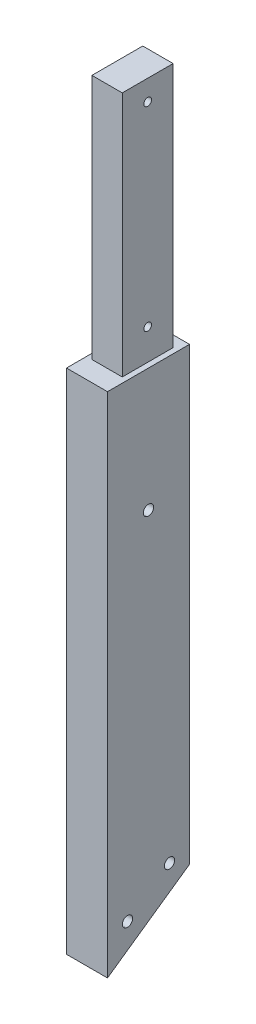
SolidWorks part; units mm, degrees
material "6061-T6 (SS)"
ref_plane "Front Plane" through (0, 0, 0) normal (0, 0, 1) x (1, 0, 0)
ref_plane "Top Plane" through (0, 0, 0) normal (0, 1, 0) x (1, 0, 0)
ref_plane "Right Plane" through (0, 0, 0) normal (1, 0, 0) x (0, 0, -1)
sketch "Sketch1" plane through (0, 0, 0) normal (1, 0, 0) x (0, 0, -1)
  line L1 (-25.4, -157.2449) -> (25.4, -157.2449)
  line L2 (-25.4, -157.2449) -> (-25.4, 157.2449)
  line L3 (-25.4, 157.2449) -> (25.4, 157.2449)
  line L4 (25.4, -157.2449) -> (25.4, 157.2449)
  line L5 (-25.4, -157.2449) -> (25.4, 157.2449) construction
  line L6 (-25.4, 157.2449) -> (25.4, -157.2449) construction
  point P0 (0, 0)
  dimension "D1" = 314.4899
  dimension "D2" = 50.8
extrude "Boss-Extrude1" add sketch "Sketch1" along normal blind 25.4
sketch "Sketch2" plane through (25.4, 0, 0) normal (1, 0, 0) x (0, 0, -1)
  line L0 (-25.4, -157.2449) -> (25.4, -121.6744)
  line L1 (25.4, -157.2449) -> (25.4, 157.2449) construction
  line L2 (25.4, -121.6744) -> (50.8, -121.6744)
  line L3 (50.8, -121.6744) -> (50.8, -172.4744)
  line L4 (50.8, -172.4744) -> (-25.4, -172.4744)
  line L5 (-25.4, -172.4744) -> (-25.4, -157.2449)
  line L6 (-25.4, -157.2449) -> (25.4, -157.2449) construction
  dimension "D1" = 35
  dimension "D2" = 76.2
  dimension "D3" = 50.8
extrude "Cut-Extrude1" cut sketch "Sketch2" against normal through all
sketch "Sketch3" plane through (25.4, 0, 0) normal (1, 0, 0) x (0, 0, -1)
  line L0 (13.004, -114.8503) -> (-13.004, -133.0614) construction
  line L1 (-13.004, -133.0614) -> (-25.4, -141.7411) construction
  line L2 (13.004, -114.8503) -> (25.4, -106.1706) construction
  line L3 (-25.4, 157.2449) -> (-25.4, -157.2449) construction
  line L4 (25.4, -121.6744) -> (25.4, 157.2449) construction
  line L6 (25.4, -121.6744) -> (-25.4, -157.2449) construction
  line L7 (-25.4, -141.7411) -> (-18.1156, -152.1443) construction
  line L8 (0, 157.2449) -> (0, 81.0449) construction
  line L9 (25.4, 157.2449) -> (-25.4, 157.2449) construction
  circle A0 centre (-13.004, -133.0614) radius 3.175
  circle A1 centre (13.004, -114.8503) radius 3.175
  circle A2 centre (0, 81.0449) radius 3.175
  dimension "D2" = 6.35
  dimension "D4" = 6.35
  dimension "D1" = 31.75
  dimension "D3" = 12.7
  dimension "D5" = 76.2
extrude "Cut-Extrude2" cut sketch "Sketch3" against normal through all
sketch "Sketch6" plane through (0, 157.2449, 0) normal (0, 1, 0) x (1, 0, 0)
  line L1 (0, 25.4) -> (25.4, 25.4)
  line L2 (0, 25.4) -> (0, -25.4)
  line L3 (0, -25.4) -> (25.4, -25.4)
  line L4 (25.4, 25.4) -> (25.4, -25.4)
extrude "Boss-Extrude3" add sketch "Sketch6" along normal blind 152.4
sketch "Sketch7" plane through (25.4, 0, 0) normal (1, 0, 0) x (0, 0, -1)
  line L0 (-25.4, 157.2449) -> (-25.4, 309.6449)
  line L2 (-25.4, 309.6449) -> (25.4, 309.6449) construction
  line L3 (-25.4, 309.6449) -> (-13.97, 309.6449)
  line L4 (-13.97, 309.6449) -> (-13.97, 163.5949)
  line L5 (39.294, 157.2449) -> (25.908, 157.2449)
  line L7 (39.294, 157.2449) -> (39.294, 309.6449)
  line L8 (39.294, 309.6449) -> (19.558, 309.6449)
  line L9 (19.558, 309.6449) -> (19.558, 163.5949)
  line L10 (-25.4, 157.2449) -> (-20.32, 157.2449)
  line L11 (-25.4, 309.6449) -> (-25.4, -157.2449) construction
  arc A0 (-20.32, 157.2449) -> (-13.97, 163.5949) centre (-20.32, 163.5949) ccw
  arc A1 (19.558, 163.5949) -> (25.908, 157.2449) centre (25.908, 163.5949) ccw
  dimension "D1" = 33.528
  dimension "D3" = 152.4
  dimension "D5" = 6.35
  dimension "D2" = 11.43
  dimension "D4" = 152.4
extrude "Cut-Extrude4" cut sketch "Sketch7" against normal through all
sketch "Sketch8" plane through (0, 0, 25.4) normal (0, 0, 1) x (1, 0, 0)
  line L0 (12.7, 309.6449) -> (12.7, 157.2449) construction
  line L1 (0, 309.6449) -> (25.4, 309.6449) construction
  line L2 (0, 157.2449) -> (25.4, 157.2449) construction
  line L3 (2.286, 309.6449) -> (-14.9016, 309.6449)
  line L4 (-14.9016, 309.6449) -> (-14.9016, 157.2449)
  line L5 (-14.9016, 157.2449) -> (-4.064, 157.2449)
  line L6 (2.286, 309.6449) -> (2.286, 163.5949)
  line L7 (23.114, 163.5949) -> (23.114, 309.6449)
  line L8 (23.114, 309.6449) -> (40.9833, 309.6449)
  line L9 (40.9833, 309.6449) -> (40.9833, 157.2449)
  line L10 (40.9833, 157.2449) -> (29.464, 157.2449)
  line L11 (2.286, 309.6449) -> (12.7, 309.6449) construction
  line L12 (12.7, 309.6449) -> (23.114, 309.6449) construction
  arc A0 (-4.064, 157.2449) -> (2.286, 163.5949) centre (-4.064, 163.5949) ccw
  arc A1 (23.114, 163.5949) -> (29.464, 157.2449) centre (29.464, 163.5949) ccw
  dimension "D2" = 6.35
  dimension "D1" = 20.828
extrude "Cut-Extrude5" cut sketch "Sketch8" against normal through all
sketch "Sketch5" plane through (23.114, 0, 0) normal (1, 0, 0) x (0, 0, -1)
  line L0 (2.794, 309.6449) -> (2.794, 157.2562) construction
  line L1 (19.558, 309.6449) -> (-13.97, 309.6449) construction
  line L4 (-25.4, 157.2449) -> (25.4, 157.2653) construction
  circle A0 centre (2.794, 296.9562) radius 2.3813
  circle A1 centre (2.794, 176.3062) radius 2.3812
  dimension "D1" = 4.7625
  dimension "D2" = 120.65
  dimension "D3" = 19.05
extrude "Cut-Extrude3" cut sketch "Sketch5" against normal through all
sketch "Sketch9" plane through (0, 309.6449, 0) normal (0, 1, 0) x (1, 0, 0)
  line L0 (22.098, 18.542) -> (3.302, 18.542)
  line L1 (3.302, 18.542) -> (3.302, -12.954)
  line L2 (3.302, -12.954) -> (22.098, -12.954)
  line L3 (22.098, -12.954) -> (22.098, 18.542)
  line L4 (22.098, 2.794) -> (12.7, 2.794)
  line L5 (12.7, -13.97) -> (12.7, 19.558)
  line L6 (2.286, -13.97) -> (23.114, -13.97) construction
  line L7 (2.286, 19.558) -> (23.114, 19.558) construction
  line L8 (12.7, 19.558) -> (12.7, 2.794)
  line L9 (12.7, 2.794) -> (12.7, -13.97)
  circle A0 centre (12.7, 2.794) radius 29.9535
  line M1 (23.114, -13.97) -> (23.114, 19.558)
  line M2 (23.114, 19.558) -> (2.286, 19.558)
  line M3 (2.286, 19.558) -> (2.286, -13.97)
  line M4 (2.286, -13.97) -> (23.114, -13.97)
extrude "Cut-Extrude6" cut sketch "Sketch9" against normal blind 152.4 and the other way through all contours A0 M1 M4 M3 M2 | L5 L2 L1 L0 M4 M2 M3 | L5 L0 L3 L2 M4 M1 M2
